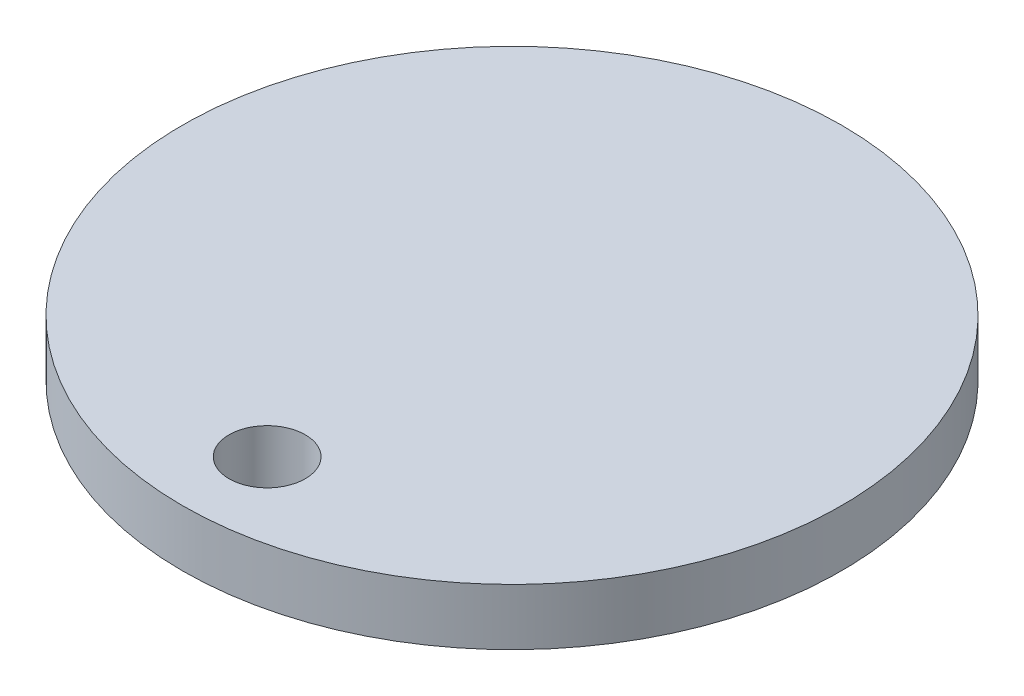
SolidWorks part; units mm, degrees
ref_plane "前视基准面" through (0, 0, 0) normal (0, 0, 1) x (1, 0, 0)
ref_plane "上视基准面" through (0, 0, 0) normal (0, 1, 0) x (1, 0, 0)
ref_plane "右视基准面" through (0, 0, 0) normal (1, 0, 0) x (0, 0, -1)
other "Configuration Table"
sketch "草图2" plane through (0, 0, 0) normal (0, 1, 0) x (1, 0, 0)
  line L0 (-27.7818, 0.5101) -> (27.7818, -0.5101) construction
  line L1 (0, 30.1933) -> (0, -30.1933) construction
  circle A0 centre (0, 0) radius 17.5
  circle A1 centre (0, -13.0022) radius 2.025
  point P6 (0, 0)
  point P8 (0, 0)
  dimension "D1" = 35
  dimension "D2" = 4.05
  dimension "D3" = 13
extrude "凸台-拉伸1" add sketch "草图2" along normal blind 3
